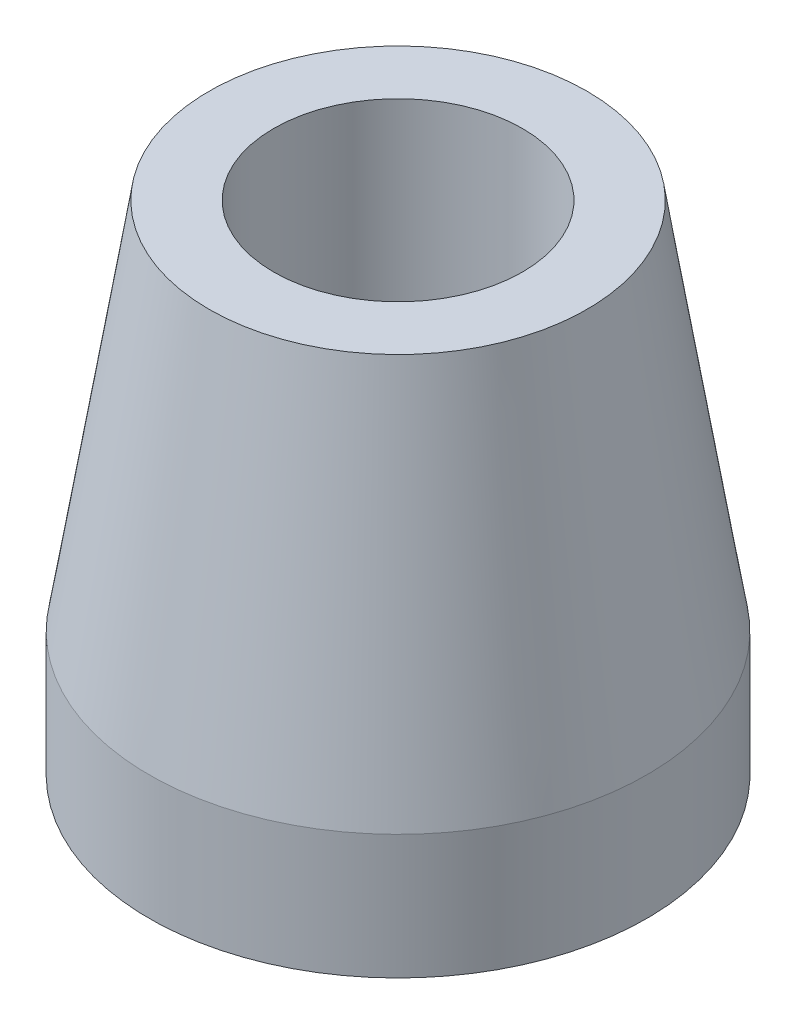
SolidWorks part; units mm, degrees
ref_plane "Front Plane" through (0, 0, 0) normal (0, 0, 1) x (1, 0, 0)
ref_plane "Top Plane" through (0, 0, 0) normal (0, 1, 0) x (1, 0, 0)
ref_plane "Right Plane" through (0, 0, 0) normal (1, 0, 0) x (0, 0, -1)
sketch "Sketch1" plane through (0, 0, 0) normal (0, 0, 1) x (1, 0, 0)
  line L0 (0, 0) -> (2.5, 0)
  line L1 (2.5, 0) -> (2.5, 7.5)
  line L2 (2.5, 7.5) -> (3.7975, 7.5)
  line L3 (3.7975, 7.5) -> (5, 0)
  line L4 (5, 0) -> (5, -2.5)
  line L5 (5, -2.5) -> (0, -2.5)
  line L6 (0, -2.5) -> (0, 0)
  dimension "D1" = 2.5
  dimension "D2" = 7.5
  dimension "D3" = 2.5
  dimension "D4" = 2.5
  dimension "D5" = 5
revolve "Revolve1" add sketch "Sketch1" angle 360 about L6
